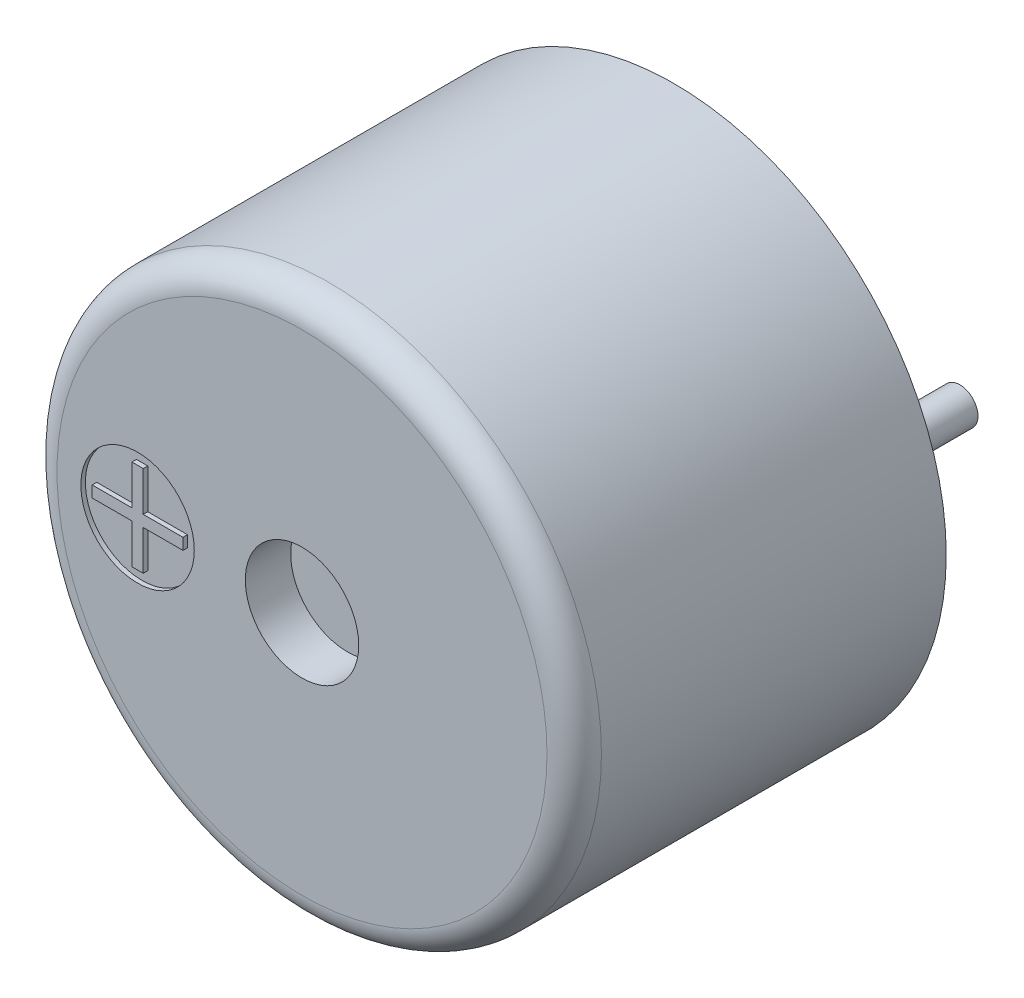
SolidWorks part; units mm, degrees
ref_plane "Plan de face" through (0, 0, 0) normal (0, 0, 1) x (1, 0, 0)
ref_plane "Plan de dessus" through (0, 0, 0) normal (0, 1, 0) x (1, 0, 0)
ref_plane "Plan de droite" through (0, 0, 0) normal (1, 0, 0) x (0, 0, -1)
sketch "Esquisse1" plane through (0, 0, 0) normal (0, 0, 1) x (1, 0, 0)
  circle A0 centre (0, 0) radius 6
  dimension "D1" = 12
extrude "corp" add sketch "Esquisse1" along normal blind 8.2
sketch "Esquisse2" plane through (0, 0, 8.2) normal (0, 0, 1) x (1, 0, 0)
  circle A0 centre (0, 0) radius 1.25
  dimension "D1" = 2.5
extrude "trou son" cut sketch "Esquisse2" against normal blind 1
sketch "Esquisse3" plane through (0, 0, 0) normal (0, 0, 1) x (1, 0, 0)
  line L0 (0, 6) -> (0, -6) construction
  line L1 (6, 0) -> (-6, 0) construction
  circle A0 centre (0, 0) radius 6 construction
  circle A1 centre (3.3, 0) radius 0.4
  circle A2 centre (-3.3, 0) radius 0.4
  dimension "D1" = 0.8
  dimension "D2" = 6.6
extrude "pins" add sketch "Esquisse3" against normal blind 3
fillet "Congé1" radius 0.6 1 edges at (6, 0, 8.2)
sketch "Esquisse4" plane through (0, 0, 8.2) normal (0, 0, 1) x (1, 0, 0)
  line L0 (-1.25, 0) -> (-6, 0) construction
  line L1 (-3.625, 0) -> (-2.4197, 1.2053) construction
  line L2 (-3.625, 1.4536) -> (-3.625, -1.7013) construction
  line L3 (-2.625, -0.125) -> (-2.625, 0.125)
  line L4 (-2.625, 0.125) -> (-3.5, 0.125)
  line L5 (-3.5, 1) -> (-3.5, 0.125)
  line L6 (-3.75, 1) -> (-3.5, 1)
  line L7 (-3.75, 1) -> (-3.75, 0.125)
  line L8 (-4.625, 0.125) -> (-3.75, 0.125)
  line L9 (-4.625, -0.125) -> (-4.625, 0.125)
  line L10 (-4.625, -0.125) -> (-3.75, -0.125)
  line L11 (-3.75, -1) -> (-3.75, -0.125)
  line L12 (-3.75, -1) -> (-3.5, -1)
  line L13 (-3.5, -1) -> (-3.5, -0.125)
  line L14 (-2.625, -0.125) -> (-3.5, -0.125)
  circle A0 centre (0, 0) radius 6 construction
  circle A2 centre (-3.625, 0) radius 1.25
  circle A3 centre (0, 0) radius 1.25 construction
  circle A4 centre (0, 0) radius 1.25 construction
  point P7 (0, 0)
  point P22 (-3.625, 1)
  point P26 (-4.625, 0)
  point P31 (-2.625, 0)
  dimension "D1" = 2.5
  dimension "D3" = 0.25
  dimension "D4" = 1
extrude "plus" cut sketch "Esquisse4" against normal blind 0.1
equation "\"DC\"= 12'diametre du corp"
equation "\"HC\"= 8.2'hauteur du corp"
equation "\"P\"= 6.6'pitch broches"
equation "\"DB\"= 0.8'diametre des broches"
equation "\"DT\"= 2.5'diametre trou son"
equation "\"D1@Esquisse1\"=\"DC\""
equation "\"D1@corp\" = \"HC\""
equation "\"D1@Esquisse2\"=\"DT\""
equation "\"D1@Esquisse3\"=\"DB\""
equation "\"D2@Esquisse3\"=\"P\""
equation "\"D1@Congé1\"= \"DC\" / 20"
equation "\"D4@Esquisse4\"=\"DT\"*0.4"
equation "\"D1@Esquisse4\"=\"DT\""
equation "\"D3@Esquisse4\"=\"DT\"/10"
